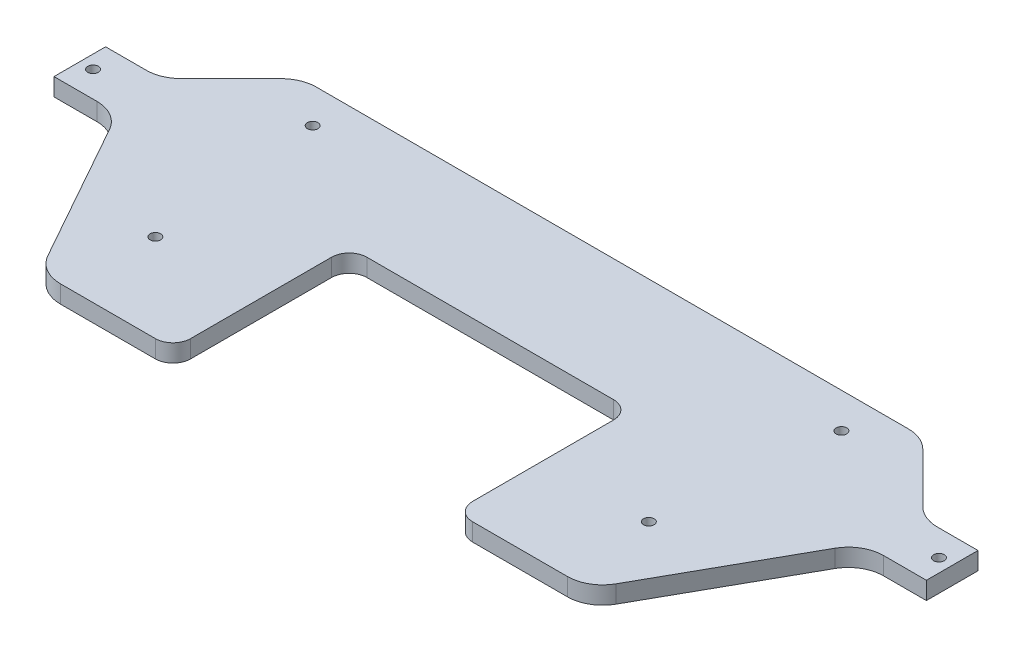
SolidWorks part; units mm, degrees
ref_plane "Alzado" through (0, 0, 0) normal (0, 0, 1) x (1, 0, 0)
ref_plane "Planta" through (0, 0, 0) normal (0, 1, 0) x (1, 0, 0)
ref_plane "Vista lateral" through (0, 0, 0) normal (1, 0, 0) x (0, 0, -1)
sketch "Croquis1" plane through (0, 0, 0) normal (0, 1, 0) x (1, 0, 0)
  line L0 (-27.8825, 0) -> (38.5584, 0) construction
  line L1 (-88.1, 42.3182) -> (88.1, 42.3182)
  line L2 (-77.75, -42.3182) -> (77.75, -42.3182)
  line L3 (-88.1, 42.3182) -> (-108.1, 22.3182)
  line L4 (-108.1, 22.3182) -> (-127.75, 22.3182)
  line L5 (0, 0) -> (0, 27.7067) construction
  line L6 (-127.75, 22.3182) -> (-127.75, 7.6818)
  line L7 (-127.75, 7.6818) -> (-105.75, 7.6818)
  line L8 (-105.75, 7.6818) -> (-77.75, -42.3182)
  line L9 (88.1, 42.3182) -> (108.1, 22.3182)
  line L10 (108.1, 22.3182) -> (127.75, 22.3182)
  line L11 (127.75, 22.3182) -> (127.75, 7.6818)
  line L12 (127.75, 7.6818) -> (105.75, 7.6818)
  line L13 (105.75, 7.6818) -> (77.75, -42.3182)
  dimension "D1" = 255.5
  dimension "D2" = 84.6363
  dimension "D3" = 19.65
  dimension "D4" = 22
  dimension "D5" = 22
  dimension "D6" = 50
  dimension "D7" = 50
  dimension "D8" = 50
  dimension "D9" = 20
  dimension "D10" = 20
extrude "Saliente-Extruir1" add sketch "Croquis1" along normal blind 5
fillet "Redondeo1" radius 10 8 edges at (88.1, 2.5, -42.3182) (-88.1, 2.5, -42.3182) (-77.75, 2.5, 42.3182) (77.75, 2.5, 42.3182) (108.1, 2.5, -22.3182) (105.75, 2.5, -7.6818) (-105.75, 2.5, -7.6818) (-108.1, 2.5, -22.3182)
sketch "Croquis2" plane through (0, 5, 0) normal (0, 1, 0) x (1, 0, 0)
  line L0 (0, 0) -> (0, -87.7887) construction
  line L1 (-119.9961, 22.3182) -> (-119.9961, 40.4374) construction
  line L2 (-112.2421, 22.3182) -> (-127.75, 22.3182) construction
  line L3 (-127.75, 15) -> (-123.2915, 15) construction
  line L4 (-127.75, 22.3182) -> (-127.75, 7.6818) construction
  line L5 (119.9961, 22.3182) -> (119.9961, 29.1715) construction
  line L6 (127.75, 22.3182) -> (112.2421, 22.3182) construction
  line L7 (115.6048, 15) -> (126.3231, 15) construction
  line L8 (83.9579, 42.3182) -> (-83.9579, 42.3182) construction
  line L10 (-71.8888, -42.3182) -> (71.8888, -42.3182) construction
  circle A0 centre (70, -17.3182) radius 1.5
  circle A1 centre (-70, -17.3182) radius 1.5
  circle A2 centre (-119.9961, 15) radius 1.5
  circle A3 centre (119.9961, 15) radius 1.5
  circle A4 centre (-75, 32.3182) radius 1.5
  circle A5 centre (75, 32.3182) radius 1.5
  circle A6 centre (-17.5, -17.3182) radius 1.5
  circle A7 centre (17.5, -17.3182) radius 1.5
  circle A8 centre (-17.5, -37.3182) radius 1.5
  circle A9 centre (17.5, -37.3182) radius 1.5
  dimension "D1" = 3
  dimension "D2" = 3
  dimension "D7" = 3
  dimension "D8" = 3
  dimension "D10" = 3
  dimension "D11" = 3
  dimension "D17" = 3
  dimension "D18" = 3
  dimension "D19" = 3
  dimension "D20" = 3
  dimension "D3" = 75
  dimension "D4" = 75
  dimension "D5" = 10
  dimension "D6" = 10
  dimension "D9" = 140
  dimension "D12" = 25
  dimension "D13" = 35
  dimension "D14" = 35
  dimension "D15" = 5
  dimension "D16" = 20
extrude "Cortar-Extruir1" cut sketch "Croquis2" against normal through all
sketch "Croquis4" plane through (0, 5, 0) normal (0, 1, 0) x (1, 0, 0)
  line L0 (-40, -42.3182) -> (-40, 7.6818)
  line L1 (-40, 7.6818) -> (40, 7.6818)
  line L2 (40, 7.6818) -> (40, -42.3182)
  line L3 (40, -42.3182) -> (-40, -42.3182)
  line L4 (0, 0) -> (0, 21.6247) construction
  line L5 (-71.8888, -42.3182) -> (71.8888, -42.3182) construction
  dimension "D1" = 80
  dimension "D2" = 50
extrude "Cortar-Extruir2" cut sketch "Croquis4" against normal through all
fillet "Redondeo2" radius 5 4 edges at (-40, 2.5, 42.3182) (40, 2.5, 42.3182) (40, 2.5, -7.6818) (-40, 2.5, -7.6818)
sketch "Croquis5" plane through (0, 5, 0) normal (0, 1, 0) x (1, 0, 0)
  line L0 (-127.75, 22.3182) -> (-127.75, 7.6818)
  line L1 (-127.75, 7.6818) -> (-123.75, 7.6818)
  line L2 (-127.75, 7.6818) -> (-111.6112, 7.6818) construction
  line L3 (-123.75, 7.6818) -> (-123.75, 22.3182)
  line L4 (-112.2421, 22.3182) -> (-127.75, 22.3182) construction
  line L5 (-123.75, 22.3182) -> (-127.75, 22.3182)
  line L6 (127.75, 22.3182) -> (127.75, 7.6818)
  line L7 (127.75, 7.6818) -> (123.75, 7.6818)
  line L8 (111.6112, 7.6818) -> (127.75, 7.6818) construction
  line L9 (123.75, 7.6818) -> (123.75, 22.3182)
  line L10 (127.75, 22.3182) -> (112.2421, 22.3182) construction
  line L11 (123.75, 22.3182) -> (127.75, 22.3182)
  dimension "D1" = 4
  dimension "D2" = 4
extrude "Cortar-Extruir3" cut sketch "Croquis5" against normal through all
